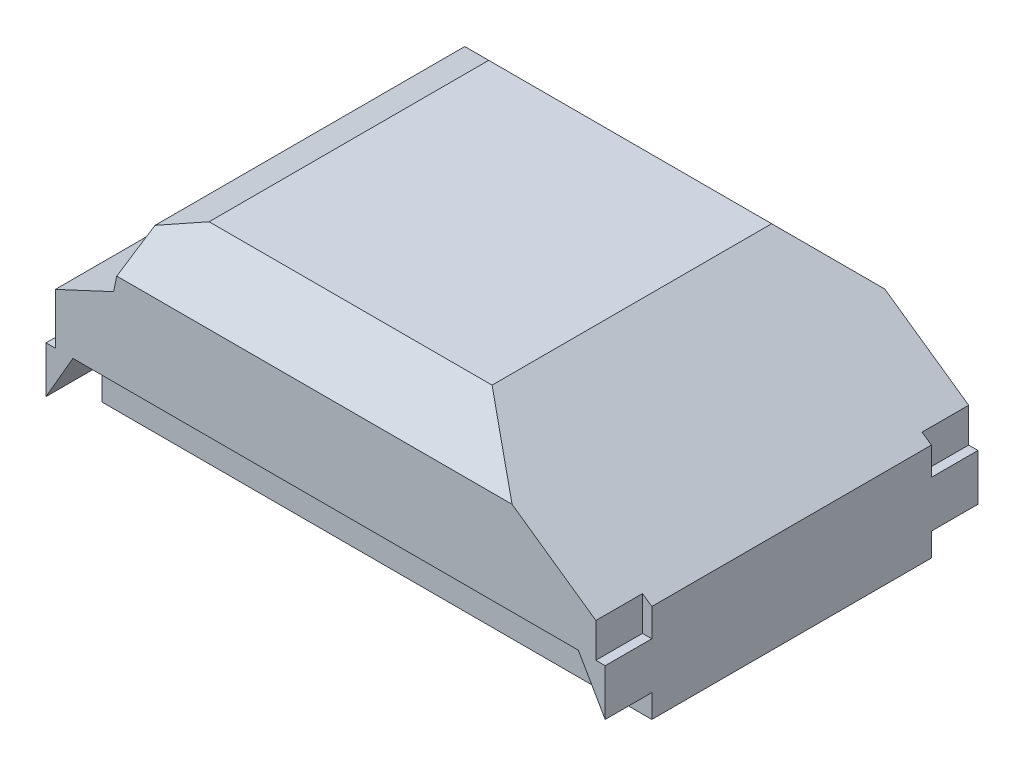
SolidWorks part; units mm, degrees
ref_plane "Front Plane" through (0, 0, 0) normal (0, 0, 1) x (1, 0, 0)
ref_plane "Top Plane" through (0, 0, 0) normal (0, 1, 0) x (1, 0, 0)
ref_plane "Right Plane" through (0, 0, 0) normal (1, 0, 0) x (0, 0, -1)
sketch "Sketch1" plane through (44.2247, 74.8917, 130.2829) normal (0, 1, 0) x (1, 0, 0)
  line L0 (-73.66, -50.8) -> (-73.66, -19.05)
  line L1 (-73.66, -19.05) -> (-76.2, -19.05)
  line L2 (-76.2, -19.05) -> (-76.2, 19.05)
  line L3 (-76.2, 19.05) -> (-73.66, 19.05)
  line L4 (-73.66, 19.05) -> (-73.66, 50.8)
  line L5 (-73.66, 50.8) -> (73.66, 50.8)
  line L6 (73.66, 50.8) -> (73.66, 38.1)
  line L7 (73.66, 38.1) -> (76.2, 38.1)
  line L8 (76.2, 38.1) -> (76.2, -38.1)
  line L9 (76.2, -38.1) -> (73.66, -38.1)
  line L10 (73.66, -38.1) -> (73.66, -50.8)
  line L11 (73.66, -50.8) -> (-73.66, -50.8)
extrude "Boss-Extrude1" add sketch "Sketch1" along normal blind 38.1
sketch "Sketch2" plane through (44.2247, 74.8917, 130.2829) normal (0, 0, 1) x (1, 0, 0)
  line L0 (-76.2, 12.7) -> (-57.7838, 21.2876)
  line L1 (-76.2, 38.1) -> (-76.2, 0) construction
  line L2 (-57.7838, 21.2876) -> (-55.0844, 33.9876)
  line L3 (-55.0844, 33.9876) -> (-44.45, 38.1)
  line L4 (-73.66, 38.1) -> (73.66, 38.1) construction
  line L5 (-44.45, 38.1) -> (-76.2, 38.1)
  line L6 (-76.2, 38.1) -> (-76.2, 12.7)
  line L7 (32.67, 38.1) -> (76.2, 7.62)
  line L8 (76.2, 38.1) -> (76.2, 0) construction
  line L9 (76.2, 7.62) -> (76.2, 38.1)
  line L10 (76.2, 38.1) -> (32.67, 38.1)
  line L11 (-73.66, 0) -> (73.66, 0) construction
  dimension "D1" = 25
  dimension "D2" = 20.32
  dimension "D3" = 25.4
  dimension "D4" = 31.75
  dimension "D5" = 12.7
  dimension "D6" = 12
  dimension "D7" = 35
  dimension "D8" = 30.48
extrude "Cut-Extrude1" cut sketch "Sketch2" against normal through all and the other way through all
sketch "Sketch3" plane through (44.2247, 74.8917, 130.2829) normal (0, 0, 1) x (1, 0, 0)
  line L0 (-76.2, 0) -> (-76.2, -12.7)
  line L1 (-76.2, -12.7) -> (-68.8677, 0)
  line L2 (-73.66, 0) -> (73.66, 0) construction
  line L3 (-68.8677, 0) -> (-76.2, 0)
  line L4 (76.2, 0) -> (76.2, -12.7)
  line L5 (76.2, -12.7) -> (68.8677, 0)
  line L6 (-73.66, 0) -> (73.66, 0) construction
  line L7 (68.8677, 0) -> (76.2, 0)
  dimension "D1" = 12.7
  dimension "D2" = 30
  dimension "D3" = 30
extrude "Boss-Extrude2" add sketch "Sketch3" along normal up to surface and the other way up to surface up to face at (28.6437, 94.2364, 181.0829) other way up to face at (28.6437, 94.2364, 79.4829)
sketch "Sketch4" plane through (44.2247, 74.8917, 130.2829) normal (1, 0, 0) x (0, 0, -1)
  line L0 (-38.1, 38.1) -> (-50.8, 25.4)
  line L1 (50.8, 38.1) -> (-50.8, 38.1) construction
  line L2 (-50.8, 38.1) -> (-50.8, 9.3985) construction
  line L3 (-50.8, 25.4) -> (-50.8, 38.1)
  line L4 (-50.8, 38.1) -> (-38.1, 38.1)
  line L5 (0, 38.1) -> (0, -12.7) construction
  line L6 (-50.8, -12.7) -> (50.8, -12.7) construction
  line L7 (38.1, 38.1) -> (50.8, 25.4)
  line L8 (50.8, 38.1) -> (38.1, 38.1)
  line L9 (50.8, 25.4) -> (50.8, 38.1)
  dimension "D1" = 12.7
  dimension "D2" = 45
extrude "Cut-Extrude2" cut sketch "Sketch4" against normal through all and the other way through all
sketch "Sketch5" plane through (0, 74.8917, 0) normal (0, -1, 0) x (1, 0, 0)
  line L1 (-29.4353, 168.3829) -> (120.4247, 168.3829)
  line L2 (-29.4353, 168.3829) -> (-29.4353, 92.1829)
  line L3 (-29.4353, 92.1829) -> (120.4247, 92.1829)
  line L4 (120.4247, 168.3829) -> (120.4247, 92.1829)
extrude "Boss-Extrude4" add sketch "Sketch5" along normal blind 19.05
